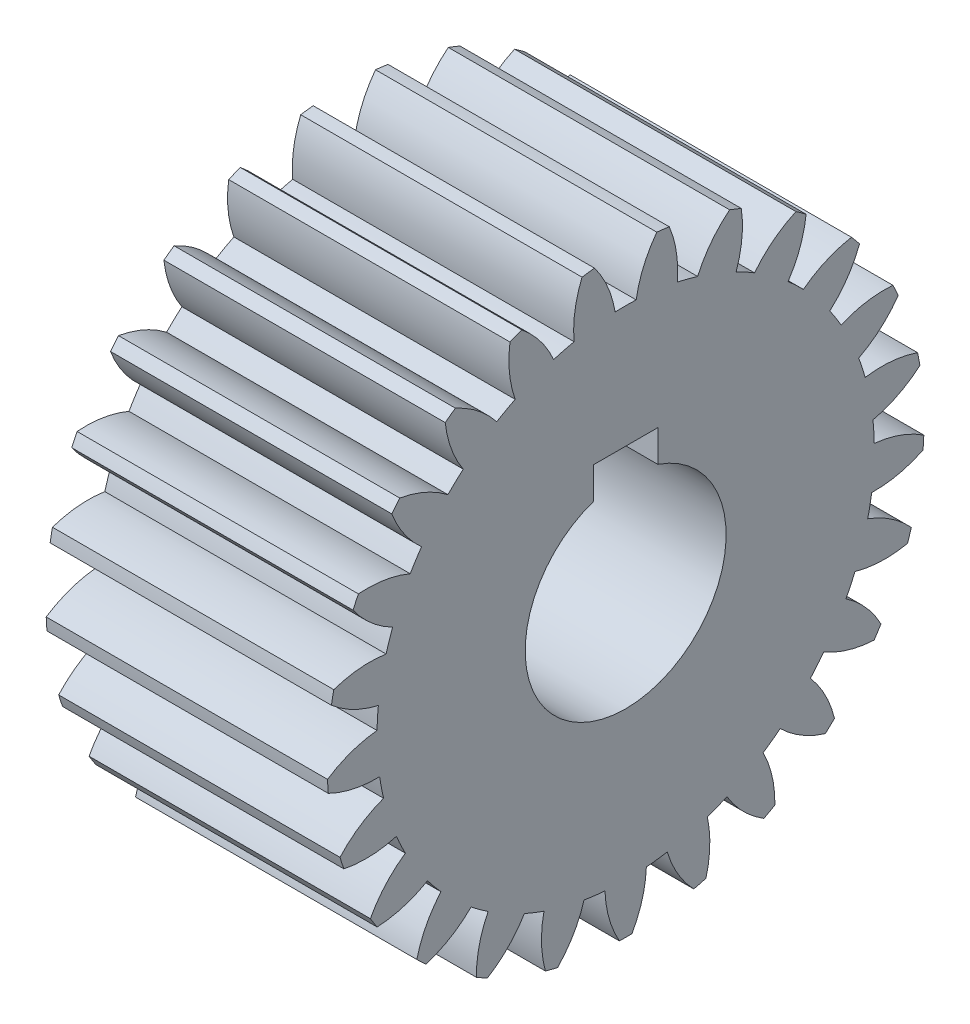
SolidWorks part; units mm, degrees
ref_plane "Plane1" through (0, 0, 0) normal (0, 0, 1) x (1, 0, 0)
ref_plane "Plane2" through (0, 0, 0) normal (0, 1, 0) x (1, 0, 0)
ref_plane "Plane3" through (0, 0, 0) normal (1, 0, 0) x (0, 0, -1)
sketch "HoldingSke" plane through (0, 0, 0) normal (0, 1, 0) x (1, 0, 0)
  line L0 (0, 0) -> (0.3296, -0.1537)
  line L1 (-15, 0) -> (100, 0) construction
  line L2 (0, 0) -> (-2.1039, 2.3779)
  line L3 (0, 0) -> (-11.863, 4.5341)
  line L4 (0, 0) -> (7.8269, 3.6497)
  line L5 (0, 0) -> (-46.8476, -17.4728)
  line L6 (0, 0) -> (-29.0137, -19.5756)
  line L7 (-2.1039, 2.3779) -> (8.6586, 51.2059)
  line L8 (-76.2, 54.61) -> (-72.9, 54.61)
  line L9 (-71.009, 38.7566) -> (-53.1078, 45.2721)
  line L10 (-76.2, 71.12) -> (104.1128, 71.12)
  line L11 (0, 0) -> (-35, 0)
  line L12 (-76.2, 101.6) -> (-76.103, 101.6)
  line L13 (24.9733, 27.94) -> (52.9518, 28.4284)
  line L14 (24.9733, 27.94) -> (24.9743, 27.94)
  line L15 (24.9733, 27.94) -> (100.4006, 29.5858)
  line L16 (-63.627, -2.75) -> (-12.827, -2.75)
  circle A0 centre (0, 0) radius 12.5
  circle A1 centre (0, 0) radius 30.9365
  circle A2 centre (0, 0) radius 37.5
  circle A3 centre (0, 0) radius 12.5
  dimension "MHD" = 61.873
  dimension "Hub_dia" = 75
  dimension "Bore" = 25
  dimension "MBD" = 25
  dimension "Num_teeth" = 25
  dimension "Pitch" = 0.3636
  dimension "Overall_len" = 50
  dimension "Show_teeth" = 25
  dimension "Thickness" = 35
  dimension "OAL" = 50.0001
  dimension "T_dim" = 3.3
  dimension "Ap" = 20
  dimension "H" = 19.05
  dimension "Pitch_radius" = 180.3128
  dimension "Width" = 35
  dimension "Backlash" = 0.097
  dimension "Addendum_fac" = 1
  dimension "Dedendum_fac" = 1.25
  dimension "Clearance_fac" = 0.25
  dimension "Dedendum_add" = 0.001
  dimension "Module" = 2.75
sketch "BasProSke" plane through (0, 0, 0) normal (0, 1, 0) x (1, 0, 0)
  line L0 (-10, 0) -> (60, 0) construction
  line L1 (0, 0) -> (0, 37.125)
  line L2 (0, 0) -> (35, 0)
  line L3 (35, 0) -> (35, 37.125)
  line L4 (35, 37.125) -> (0, 37.125)
  dimension "Thickness" = 35
  dimension "Diameter" = 74.25
revolve "Base-Revolve" add sketch "BasProSke" angle 360 about L0
sketch "TooCutSke" plane through (0, 0, 0) normal (1, 0, 0) x (0, 0, -1)
  line L1 (0, 0) -> (0, 107) construction
  line L2 (0, 0) -> (-2.3281, 34.2961) construction
  line L3 (0, 0) -> (-8.6022, 68.0936) construction
  line L4 (-2.3281, 34.2961) -> (-4.3011, 34.0468) construction
  arc A0 (1.3087, 30.9088) -> (-1.3087, 30.9088) centre (0, 0) ccw
  arc A1 (3.893, 36.9459) -> (-3.893, 36.9459) centre (0, 0) ccw
  circle A2 centre (0, 0) radius 34.375 construction
  circle A3 centre (0, 0) radius 32.3019 construction
  arc A4 (-1.3087, 30.9088) -> (-3.893, 36.9459) centre (-14.8757, 28.6728) ccw
  arc A5 (3.893, 36.9459) -> (1.3087, 30.9088) centre (14.8757, 28.6728) ccw
  dimension "Root_dia" = 61.873
  dimension "Overcut_dia" = 74.3008
  dimension "Pitch_dia" = 68.75
  dimension "Base_dia" = 64.6039
  dimension "Flank_rad" = 13.75
  dimension "Half_ang" = 7.2
  dimension "Half_CT" = 1.9887
extrude "ToothCut" cut sketch "TooCutSke" along normal through all
fillet "Breaks" [suppressed] radius 0.055
fillet "RootFillets" [suppressed] radius 0.6885
pattern_circular "TeethCuts" count 25 every 14.4 about axis through (-10, 0, 0) along (1, 0, 0) of "ToothCut", "RootFillets", "Breaks"
sketch "HubNeaOneSke" plane through (0, 0, 0) normal (-1, 0, 0) x (0, 0, 1)
  circle A0 centre (0, 0) radius 30.9365
  dimension "Diameter" = 61.873
extrude "HubNearOne" [suppressed] add sketch "HubNeaOneSke" along normal blind 15.0001
sketch "HubNeaBotSke" plane through (0, 0, 0) normal (-1, 0, 0) x (0, 0, 1)
  circle A0 centre (0, 0) radius 30.9365
  dimension "Diameter" = 61.873
extrude "HubNearBoth" [suppressed] add sketch "HubNeaBotSke" along normal blind 7.5
ref_plane "FarPln" through (35, 0, 0) normal (1, 0, 0) x (0, 0, -1)
sketch "HubFarSke" plane through (35, 0, 0) normal (1, 0, 0) x (0, 0, -1)
  circle A0 centre (0, 0) radius 30.9365
  dimension "Diameter" = 61.873
extrude "HubFar" [suppressed] add sketch "HubFarSke" along normal blind 7.5
sketch "BorSke" plane through (0, 0, 0) normal (1, 0, 0) x (0, 0, -1)
  circle A0 centre (0, 0) radius 12.5
  dimension "Diameter" = 25
extrude "Bore" cut sketch "BorSke" along normal mid plane 100.0001
sketch "KeySke" plane through (0, 0, 0) normal (1, 0, 0) x (0, 0, -1)
  line L0 (-4, 0) -> (-4, 15.8)
  line L1 (-4, 15.8) -> (4, 15.8)
  line L2 (4, 15.8) -> (4, 0)
  line L3 (0, 0) -> (0, 34) construction
  line L4 (-4, 0) -> (4, 0)
  dimension "Offset" = 15.8
  dimension "Width" = 8
extrude "Keyway" cut sketch "KeySke" along normal mid plane 100.0001
pattern_circular "Keyway2" [suppressed] count 2 every 90 about axis through (-10, 0, 0) along (1, 0, 0)
equation "' \"Module@HoldingSke\" = 6.35"
equation "' \"Num_teeth@HoldingSke\" = 12"
equation "' \"Ap@HoldingSke\" =  20"
equation "' \"Ap@HoldingSke\" = 20"
equation "' \"Width@HoldingSke\" = 0.5 * 25.4"
equation "' \"Hub_dia@HoldingSke\"= 1 * 25.4"
equation "' \"Hub_dia@HoldingSke\" = 1 * 25.4"
equation "' \"Overall_len@HoldingSke\" = 1.0 * 25.4"
equation "' \"Bore@HoldingSke\" = 0.75 * 25.4"
equation "' \"T_dim@HoldingSke\" = 0.1 * 25.4"
equation "' \"Width@KeySke\" = 0.25 * 25.4"
equation "' \"Show_teeth@HoldingSke\" = 13"
equation "' \"Backlash@HoldingSke\" = 0.009 * 25.4"
equation "' \"Addendum_fac@HoldingSke\" = 1.0"
equation "' \"Dedendum_fac@HoldingSke\" = 1.25"
equation "' \"Dedendum_add@HoldingSke\" = 0.00005 * 25.4"
equation "' \"Clearance_fac@HoldingSke\" = 0.25"
equation "\"Pitch@HoldingSke\" = 1 / \"Module@HoldingSke\""
equation "\"Overcut_dia@TooCutSke\" = (\"Num_teeth@HoldingSke\" + 2 * \"Addendum_fac@HoldingSke\") / \"Pitch@HoldingSke\" + 0.002 * 25.4"
equation "\"Pitch_dia@TooCutSke\" = \"Num_teeth@HoldingSke\" / \"Pitch@HoldingSke\""
equation "\"Base_dia@TooCutSke\" = \"Num_teeth@HoldingSke\" / \"Pitch@HoldingSke\" * cos((\"Ap@HoldingSke\"  * 3.14159265 / 180))"
equation "\"Root_dia@TooCutSke\" = (\"Num_teeth@HoldingSke\" + 2) / \"Pitch@HoldingSke\" - 2 * (\"Addendum_fac@HoldingSke\" + \"Dedendum_fac@HoldingSke\") / \"Pitch@HoldingSke\" - \"Dedendum_add@HoldingSke\" * 2"
equation "\"Half_ang@TooCutSke\" = 180 / \"Num_teeth@HoldingSke\""
equation "\"Half_CT@TooCutSke\" = \"Num_teeth@HoldingSke\" / \"Pitch@HoldingSke\" * sin((3.14159265 / 2 / \"Num_teeth@HoldingSke\")) / 2 - 7 * \"Backlash@HoldingSke\" / 4"
equation "\"Flank_rad@TooCutSke\" = \"Num_teeth@HoldingSke\" / \"Pitch@HoldingSke\" / 5"
equation "\"Radius@RootFillets\" = \"Clearance_fac@HoldingSke\" / \"Pitch@HoldingSke\" + \"Dedendum_add@HoldingSke\""
equation "\"Break_rad@Breaks\" = 0.02 / \"Pitch@HoldingSke\""
equation "\"Thickness@HoldingSke\" = \"Width@HoldingSke\""
equation "\"OAL@HoldingSke\" = \"Thickness@HoldingSke\""
equation "\"MHD@HoldingSke\" = (\"Num_teeth@HoldingSke\" + 2) / \"Pitch@HoldingSke\" - 2 * (\"Addendum_fac@HoldingSke\" + \"Dedendum_fac@HoldingSke\")  / \"Pitch@HoldingSke\" - \"Dedendum_add@HoldingSke\" * 2"
equation "\"MBD@HoldingSke\" = (\"Num_teeth@HoldingSke\" + 2) / \"Pitch@HoldingSke\" - 2 * (\"Addendum_fac@HoldingSke\" + \"Dedendum_fac@HoldingSke\")  / \"Pitch@HoldingSke\" - \"Dedendum_add@HoldingSke\" * 2 - 0.002 * 25.4"
equation "\"MHD@HoldingSke\" = ((sgn( \"MHD@HoldingSke\" - \"Hub_dia@HoldingSke\" )-1)*( \"MHD@HoldingSke\" - \"Hub_dia@HoldingSke\" ))/-2+ \"Hub_dia@HoldingSke\""
equation "\"MBD@HoldingSke\" = ((sgn( \"MBD@HoldingSke\" - \"Bore@HoldingSke\" )-1)*( \"MBD@HoldingSke\" - \"Bore@HoldingSke\" ))/-2+ \"Bore@HoldingSke\""
equation "\"OAL@HoldingSke\" = ((sgn( \"OAL@HoldingSke\" - \"Overall_len@HoldingSke\" )+1)*( \"OAL@HoldingSke\" - \"Overall_len@HoldingSke\" ))/2 + \"Overall_len@HoldingSke\" + 0.000002 * 25.4"
equation "\"Num_teeth@TeethCuts\" = int( \"Show_teeth@HoldingSke\" ) + 1"
equation "\"Num_teeth@TeethCuts\" = ((sgn( \"Num_teeth@TeethCuts\" - \"Num_teeth@HoldingSke\" )-1)*( \"Num_teeth@TeethCuts\" - \"Num_teeth@HoldingSke\" ))/-2+ \"Num_teeth@HoldingSke\""
equation "\"Num_teeth@TeethCuts\" = ((sgn( \"Num_teeth@TeethCuts\" - 2.0)+1)*( \"Num_teeth@TeethCuts\" - 2.0))/2 +2.0"
equation "\"Angle@TeethCuts\" = 360.0 / \"Num_teeth@HoldingSke\""
equation "\"Diameter@BasProSke\" = (\"Num_teeth@HoldingSke\" + 2 * \"Addendum_fac@HoldingSke\") / \"Pitch@HoldingSke\""
equation "\"Thickness@BasProSke\"  = \"Thickness@HoldingSke\""
equation "' \"Fillet_rad@BasProSke\" =  \"Thickness@HoldingSke\" * 0.05"
equation "' \"Fillet_rad@BasProSke\" = \"Thickness@HoldingSke\" * 0.05"
equation "\"MHD@HoldingSke\" = ((sgn( \"MHD@HoldingSke\" - \"Root_dia@TooCutSke\" )-1)*( \"MHD@HoldingSke\" - \"Root_dia@TooCutSke\" ))/-2+ \"Root_dia@TooCutSke\""
equation "\"Diameter@HubNeaOneSke\" = \"MHD@HoldingSke\""
equation "\"Length@HubNearOne\" = \"OAL@HoldingSke\" - \"Thickness@BasProSke\""
equation "\"Diameter@HubNeaBotSke\" = \"MHD@HoldingSke\""
equation "\"Length@HubNearBoth\" = ( \"OAL@HoldingSke\" - \"Thickness@BasProSke\" ) / 2.0"
equation "\"Thickness@FarPln\" = \"Thickness@BasProSke\""
equation "\"Diameter@HubFarSke\" = \"MHD@HoldingSke\""
equation "\"Length@HubFar\" = ( \"OAL@HoldingSke\" - \"Thickness@BasProSke\" ) / 2.0"
equation "\"Diameter@BorSke\" = \"MBD@HoldingSke\""
equation "\"D1@Bore\" = \"OAL@HoldingSke\" * 2.0"
equation "\"D1@Keyway\" = \"OAL@HoldingSke\" * 2.0"
equation "\"Offset@KeySke\" = \"T_dim@HoldingSke\" + \"MBD@HoldingSke\" / 2.0"
